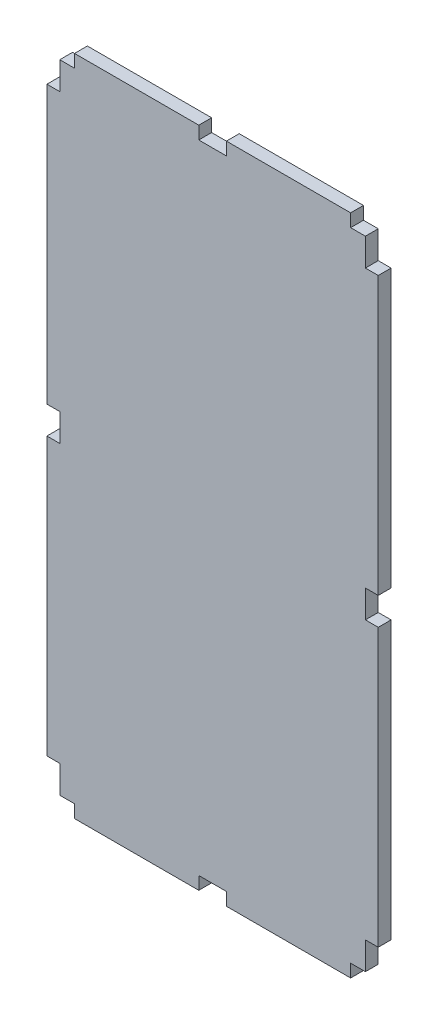
SolidWorks part; units mm, degrees
material "Oak"
ref_plane "Front Plane" through (0, 0, 0) normal (0, 0, 1) x (1, 0, 0)
ref_plane "Top Plane" through (0, 0, 0) normal (0, 1, 0) x (1, 0, 0)
ref_plane "Right Plane" through (0, 0, 0) normal (1, 0, 0) x (0, 0, -1)
sketch "Base_Sketch" plane through (0, 0, 0) normal (0, 0, 1) x (1, 0, 0)
  line L1 (-25.4, 457.2) -> (279.4, 457.2)
  line L2 (-25.4, 457.2) -> (-25.4, -152.4)
  line L3 (-25.4, -152.4) -> (279.4, -152.4)
  line L4 (279.4, 457.2) -> (279.4, -152.4)
  line L5 (-25.4, 457.2) -> (279.4, -152.4) construction
  line L6 (-25.4, -152.4) -> (279.4, 457.2) construction
  line L7 (-25.4, 457.2) -> (279.4, 457.2) construction
  line L8 (-25.4, -152.4) -> (279.4, -152.4) construction
  line L9 (-25.4, 457.2) -> (-25.4, -152.4) construction
  line L10 (279.4, 457.2) -> (279.4, -152.4) construction
extrude "Boss-Extrude1" add sketch "Base_Sketch" along normal blind 11.81
ref_plane "Mid_Plane" through (0, 152.4, 0) normal (0, -1, 0) x (-1, 0, 0)
sketch "Joint_X" plane through (0, 0, 11.81) normal (0, 0, 1) x (1, 0, 0)
  line L1 (-25.4, -152.4) -> (0, -152.4)
  line L2 (-25.4, -152.4) -> (-25.4, -140.59)
  line L3 (-25.4, -140.59) -> (0, -140.59)
  line L4 (0, -152.4) -> (0, -140.59)
  point P5 (0, -146.495)
  dimension "D1" = 11.81
  dimension "D2" = 25.4
extrude "Cut-Extrude1" cut sketch "Joint_X" against normal through all
pattern_linear "LPattern1" count 3 spacing 139.7 along (1, 0, 0) of "Cut-Extrude1"
mirror "Mirror1" about plane through (0, 152.4, 0) normal (0, -1, 0) of "Cut-Extrude1", "LPattern1"
ref_plane "Mid_Plane_1" through (127, 0, 0) normal (-1, 0, 0) x (0, 0, 1)
sketch "Joint_Y" plane through (0, 0, 11.81) normal (0, 0, 1) x (1, 0, 0)
  line L1 (-25.4, -140.59) -> (-13.59, -140.59)
  line L2 (-25.4, -140.59) -> (-25.4, -115.19)
  line L3 (-25.4, -115.19) -> (-13.59, -115.19)
  line L4 (-13.59, -140.59) -> (-13.59, -115.19)
  dimension "D1" = 11.81
  dimension "D2" = 25.4
extrude "Cut-Extrude2" cut sketch "Joint_Y" against normal through all
pattern_linear "LPattern3" count 3 spacing 280.29 along (0, 1, 0) of "Cut-Extrude2"
mirror "Mirror4" about plane through (127, 0, 0) normal (-1, 0, 0) of "Cut-Extrude2", "LPattern3"
equation "\"Material_Thickness\"= \"Material_Thickness@Petrov.Assembly\""
equation "\"D1@Boss-Extrude1\"=\"Material_Thickness\""
equation "\"D1@Joint_X\" = \"Material_Thickness\""
equation "\"D1@Joint_Y\" = \"Material_Thickness\""
equation "\"Num_Joints\"= \"Cover_Num_Joints@Petrov.Assembly\""
equation "\"D1@LPattern1\"=\"Num_Joints\""
equation "\"D1@LPattern3\"=\"Num_Joints\""
equation "\"Joint_Size\"= \"Cover_Joint_Size@Petrov.Assembly\""
equation "\"D2@Joint_X\"=\"Joint_Size\""
equation "\"D2@Joint_Y\"=\"Joint_Size\""
